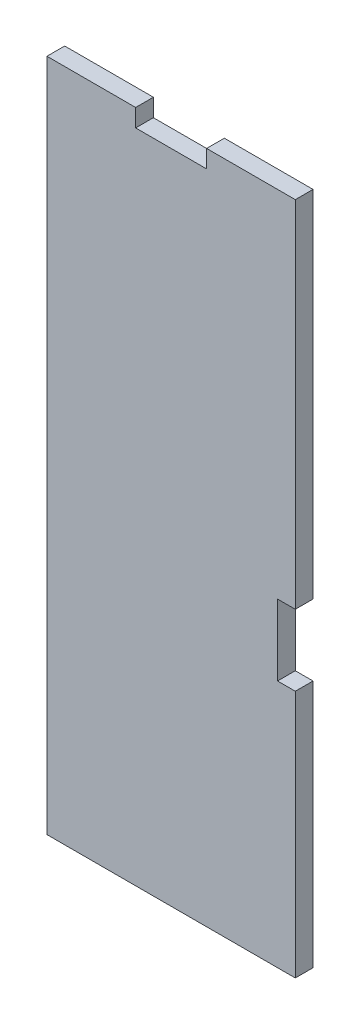
SolidWorks part; units mm, degrees
ref_plane "Front Plane" through (0, 0, 0) normal (0, 0, 1) x (1, 0, 0)
ref_plane "Top Plane" through (0, 0, 0) normal (0, 1, 0) x (1, 0, 0)
ref_plane "Right Plane" through (0, 0, 0) normal (1, 0, 0) x (0, 0, -1)
sketch "Sketch1" plane through (0, 0, 0) normal (0, 0, 1) x (1, 0, 0)
  line L0 (-2.8376, 46.0832) -> (-15.3376, 46.0832)
  line L1 (-2.8376, -48.9168) -> (-37.8376, -48.9168)
  line L2 (-37.8376, -48.9168) -> (-37.8376, 46.0832)
  line L3 (-2.8376, 46.0832) -> (-2.8376, -3.9168)
  line L4 (-2.8376, -3.9168) -> (-5.3376, -3.9168)
  line L5 (-5.3376, -3.9168) -> (-5.3376, -13.9168)
  line L6 (-5.3376, -13.9168) -> (-2.8376, -13.9168)
  line L7 (-2.8376, -13.9168) -> (-2.8376, -48.9168)
  line L8 (-25.3376, 46.0832) -> (-37.8376, 46.0832)
  line L9 (-25.3376, 43.5832) -> (-15.3376, 43.5832)
  line L10 (-25.3376, 43.5832) -> (-25.3376, 46.0832)
  line L12 (-15.3376, 43.5832) -> (-15.3376, 46.0832)
  line L13 (-37.8376, 46.0832) -> (-2.8376, -48.9168) construction
  line L14 (-2.8376, 46.0832) -> (-37.8376, -48.9168) construction
  point P7 (-20.3376, 46.0832)
  dimension "D1" = 35
  dimension "D2" = 2.5
  dimension "D3" = 10
  dimension "D4" = 95
  dimension "D5" = 50
  dimension "D6" = 35
  dimension "D7" = 12.5
  dimension "D8" = 12.5
extrude "Boss-Extrude1" add sketch "Sketch1" along normal blind 2.5
